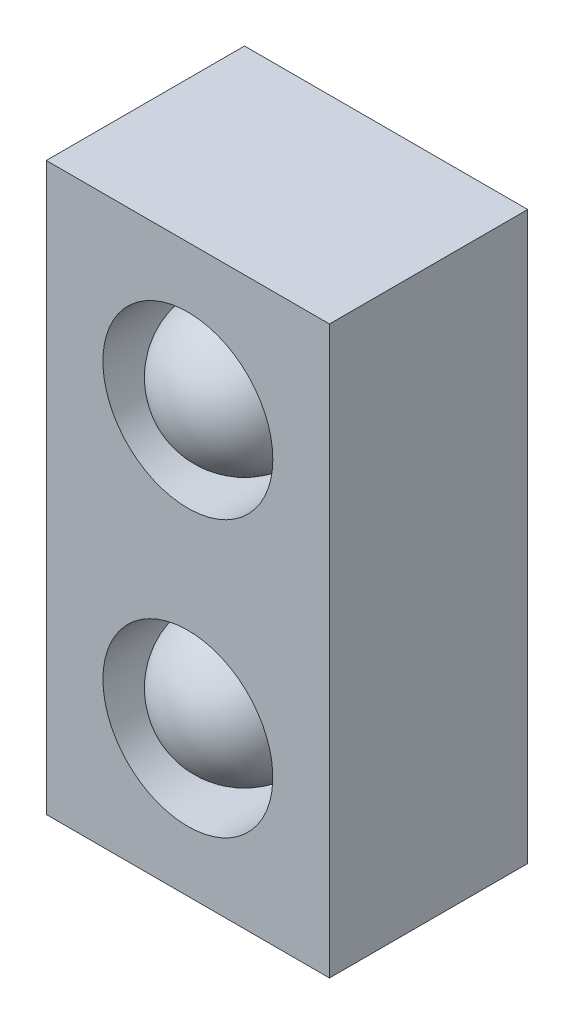
SolidWorks part; units mm, degrees
ref_plane "Front Plane" through (0, 0, 0) normal (0, 0, 1) x (1, 0, 0)
ref_plane "Top Plane" through (0, 0, 0) normal (0, 1, 0) x (1, 0, 0)
ref_plane "Right Plane" through (0, 0, 0) normal (1, 0, 0) x (0, 0, -1)
sketch "Sketch2" plane through (0, 0, 0) normal (0, 0, 1) x (1, 0, 0)
  line L0 (0, 0) -> (9.6061, 0) construction
  line L1 (-5, -10) -> (5, -10)
  line L2 (-5, -10) -> (-5, 10)
  line L3 (-5, 10) -> (5, 10)
  line L4 (5, -10) -> (5, 10)
  line L5 (-5, -10) -> (5, 10) construction
  line L6 (-5, 10) -> (5, -10) construction
  circle A0 centre (0, 4.8651) radius 3
  circle A1 centre (0, -4.8651) radius 3
  point P0 (0, 0)
  dimension "D1" = 10
  dimension "D2" = 20
extrude "Boss-Extrude1" add sketch "Sketch2" along normal blind 7
sketch "Sketch3" plane through (0, 0, 0) normal (0, 0, -1) x (-1, 0, 0)
  circle A0 centre (0, 4.8651) radius 2.5
extrude "Boss-Extrude2" add sketch "Sketch3" against normal blind 5 separate body
ref_plane "Plane1" through (0, 0, 5) normal (0, 0, 1) x (1, 0, 0)
sketch "Sketch4" plane through (0, 0, 5) normal (0, 0, 1) x (1, 0, 0)
  line L0 (-2.5, 4.8651) -> (2.5, 4.8651) construction
  line L1 (-2.5, 4.8651) -> (2.5, 4.8651)
  arc A0 (2.5, 4.8651) -> (-2.5, 4.8651) centre (0, 4.8651) ccw
revolve "Revolve1" add sketch "Sketch4" angle 180 about L0
pattern_linear "LPattern1" count 2 spacing 9.5 along (0, -1, 0) of "Boss-Extrude2", "Revolve1"
